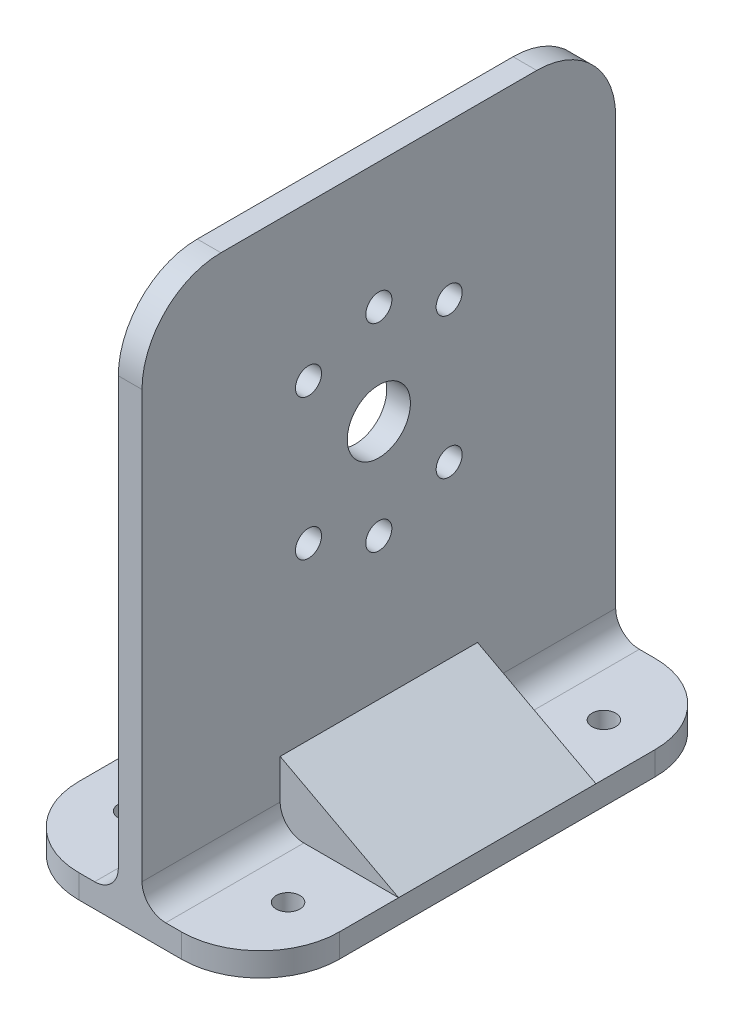
SolidWorks part; units mm, degrees
ref_plane "前视基准面" through (0, 0, 0) normal (0, 0, 1) x (1, 0, 0)
ref_plane "上视基准面" through (0, 0, 0) normal (0, 1, 0) x (1, 0, 0)
ref_plane "右视基准面" through (0, 0, 0) normal (1, 0, 0) x (0, 0, -1)
other "Configuration Table"
sketch "草图1" plane through (0, 0, 0) normal (0, 0, 1) x (1, 0, 0)
  line L1 (-1.5, -35) -> (1.5, -35)
  line L2 (-1.5, -35) -> (-1.5, 35)
  line L3 (-1.5, 35) -> (1.5, 35)
  line L4 (1.5, -35) -> (1.5, 35)
  line L5 (-1.5, -35) -> (1.5, 35) construction
  line L6 (-1.5, 35) -> (1.5, -35) construction
  point P0 (0, 0)
  dimension "D1" = 3
  dimension "D2" = 70
extrude "凸台-拉伸1" add sketch "草图1" along normal blind 60
sketch "草图2" plane through (-1.5, 0, 0) normal (-1, 0, 0) x (0, 0, 1)
  line L0 (60, 35) -> (60, -35) construction
  line L1 (0, -35) -> (60, -35)
  line L2 (0, -35) -> (0, -32)
  line L3 (0, -32) -> (60, -32)
  line L4 (60, -35) -> (60, -32)
  dimension "D1" = 3
extrude "凸台-拉伸2" add sketch "草图2" along normal blind 15 contours L2 L1 L4 L3
mirror "镜向1" about plane through (0, 0, 0) normal (1, 0, 0) of "凸台-拉伸2"
fillet "圆角2" radius 10 2 edges at (0, 35, 0) (0, 35, 60)
sketch "草图3" plane through (1.5, 0, 0) normal (1, 0, 0) x (0, 0, -1)
  line L0 (-30, 6.5) -> (-72.0943, 48.5943) construction
  line L6 (-30, 41.6874) -> (-30, -38.0819) construction
  line L7 (-68.8276, 6.5) -> (7.3198, 6.5) construction
  circle A0 centre (-38.9095, -2.4095) radius 1.65
  circle A1 centre (-21.0905, -2.4095) radius 1.65
  circle A2 centre (-30, 6.5) radius 4
  circle A3 centre (-38.9095, 15.4095) radius 1.65
  circle A6 centre (-21.0905, 15.4095) radius 1.65
  dimension "D1" = 8
  dimension "D3" = 3.3
  dimension "D2" = 12.6
  dimension "D4" = 45
extrude "切除-拉伸1" cut sketch "草图3" against normal up to next
sketch "草图5" plane through (0, -35, 0) normal (0, 1, 0) x (1, 0, 0)
  line L4 (-25, 10) -> (-25, -70)
  line L5 (-15, -80) -> (15, -80)
  line L6 (25, -70) -> (25, 10)
  line L7 (15, 20) -> (-15, 20)
  line L8 (-25, 10) -> (-25, -70)
  line L9 (-15, -80) -> (15, -80)
  line L10 (25, -70) -> (25, 10)
  line L11 (15, 20) -> (-15, 20)
  circle A0 centre (10, -10) radius 1.5 construction
  circle A1 centre (10, -10) radius 1.5
  arc A4 (-25, -70) -> (-15, -80) centre (-15, -70) ccw
  arc A5 (15, -80) -> (25, -70) centre (15, -70) ccw
  arc A6 (25, 10) -> (15, 20) centre (15, 10) ccw
  arc A7 (-15, 20) -> (-25, 10) centre (-15, 10) ccw
  arc A8 (-25, -70) -> (-15, -80) centre (-15, -70) ccw
  arc A9 (15, -80) -> (25, -70) centre (15, -70) ccw
  arc A10 (25, 10) -> (15, 20) centre (15, 10) ccw
  arc A11 (-15, 20) -> (-25, 10) centre (-15, 10) ccw
  circle M10 centre (10, -10) radius 1.5
  dimension "D1" = 0
extrude "切除-拉伸4" cut sketch "草图5" along normal blind 3 contours M10
fillet "圆角3" radius 10 4 edges at (16.5, -33.5, 60) (16.5, -33.5, 0) (-16.5, -33.5, 60) (-16.5, -33.5, 0)
mirror "镜向2" about plane through (0, 0, 0) normal (1, 0, 0) of "切除-拉伸4" second plane through (0, 0, 0) second plane normal (0, 1, 0)
sketch "草图6" plane through (0, -32, 0) normal (0, 1, 0) x (1, 0, 0)
  line L0 (-16.5, -30) -> (16.5, -30) construction
  line L1 (-16.5, -10) -> (-16.5, -50) construction
  line L2 (16.5, -10) -> (16.5, -50) construction
ref_plane "基准面1" through (0, 0, 30) normal (0, 0, 1) x (1, 0, 0)
mirror "镜向3" about plane through (0, 0, 30) normal (0, 0, 1) of "切除-拉伸4", "镜向2"
sketch "草图7" plane through (-1.5, 0, 0) normal (-1, 0, 0) x (0, 0, 1)
  line L0 (30, 6.5) -> (70.1982, 6.5) construction
  line L1 (30, 6.5) -> (-19.4247, 6.5) construction
  line L2 (30, 6.5) -> (30, 37.2743) construction
  circle A2 centre (30, 19.05) radius 1.65
  circle A3 centre (30, -6.05) radius 1.65
  dimension "D1" = 3.3
  dimension "D2" = 25.1
extrude "切除-拉伸5" cut sketch "草图7" against normal blind 10
sketch "草图8" plane through (0, 0, 30) normal (0, 0, 1) x (1, 0, 0)
  line L0 (1.5, -24) -> (16.5, -32)
  line L1 (1.5, -32) -> (1.5, 25) construction
  line L2 (16.5, -32) -> (1.5, -32)
  line L3 (-16.5, -32) -> (16.5, -32) construction
  line L4 (1.5, -32) -> (1.5, -24)
  dimension "D1" = 8
extrude "凸台-拉伸3" add sketch "草图8" along normal mid plane 25
mirror "镜向4" about plane through (0, 0, 0) normal (1, 0, 0) of "凸台-拉伸3"
fillet "圆角4" radius 3 4 edges at (-1.5, -32, 8.75) (-1.5, -32, 51.25) (1.5, -32, 51.25) (1.5, -32, 8.75)
